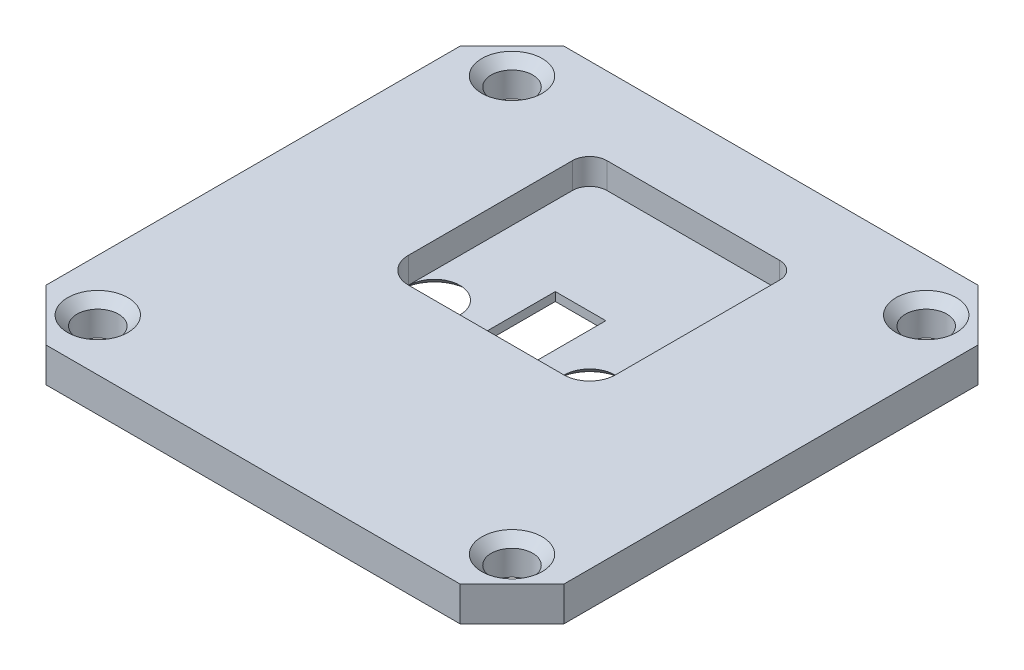
SolidWorks part; units mm, degrees
ref_plane "Front Plane" through (0, 0, 0) normal (0, 0, 1) x (1, 0, 0)
ref_plane "Top Plane" through (0, 0, 0) normal (0, 1, 0) x (1, 0, 0)
ref_plane "Right Plane" through (0, 0, 0) normal (1, 0, 0) x (0, 0, -1)
sketch "Sketch1" plane through (0, 0, 0) normal (0, 1, 0) x (1, 0, 0)
  line L0 (-11.2931, 29.7045) -> (12.7069, 29.7045)
  line L1 (12.7069, 29.7045) -> (15.7069, 26.7045)
  line L2 (15.7069, 26.7045) -> (15.7069, 2.7045)
  line L3 (15.7069, 2.7045) -> (12.7069, -0.2955)
  line L4 (12.7069, -0.2955) -> (-11.2931, -0.2955)
  line L5 (-11.2931, -0.2955) -> (-14.2931, 2.7045)
  line L6 (-14.2931, 26.7045) -> (-14.2931, 2.7045)
  line L7 (-11.2931, 29.7045) -> (-14.2931, 26.7045)
  line L9 (2.2069, 18.6402) -> (-0.719, 18.6402)
  line L10 (2.2069, 18.6402) -> (2.2069, 13.7386)
  line L11 (2.2069, 13.7386) -> (-0.719, 13.7386)
  line L12 (-0.719, 18.6402) -> (-0.719, 13.7386)
  dimension "D1" = 2.2069
  dimension "D2" = 12.7069
  dimension "D3" = 0.719
  dimension "D4" = 11.2931
  dimension "D5" = 14.2931
  dimension "D6" = 2.7045
extrude "Boss-Extrude1" add sketch "Sketch1" along normal blind 2
sketch "Sketch7" plane through (0, 2, 0) normal (0, 1, 0) x (1, 0, 0)
  line L0 (-14.2931, 26.7045) -> (-14.2931, 2.7045) construction
  line L1 (12.7069, 29.7045) -> (-11.2931, 29.7045) construction
  line L2 (15.7069, 2.7045) -> (15.7069, 26.7045) construction
  line L3 (-11.2931, -0.2955) -> (12.7069, -0.2955) construction
  circle A0 centre (-11.2931, 26.7045) radius 0.551
  circle A1 centre (-11.2931, 2.7045) radius 0.6431
  circle A2 centre (12.7069, 26.7045) radius 0.6077
  circle A3 centre (12.7069, 2.7045) radius 0.4297
  point P0 (-11.2931, 26.7045)
  point P2 (-11.2931, 2.7045)
  point P4 (12.7069, 26.7045)
  point P6 (12.7069, 2.7045)
  dimension "D9" = 1.102
  dimension "D10" = 1.2155
  dimension "D11" = 0.8595
  dimension "D12" = 1.2861
  dimension "D1" = 3
  dimension "D2" = 3
  dimension "D3" = 3
  dimension "D4" = 3
  dimension "D5" = 3
  dimension "D6" = 3
  dimension "D7" = 3
  dimension "D8" = 3
hole_wizard "CSK for M2 Flat Head Machine Screw2" positions "Sketch7" profile "Sketch8" countersink size "M2" standard "ANSI Metric"
sketch "Sketch8" plane through (-11.2931, 2, -26.7045) normal (1, 0, 0) x (0, 0, 1)
  line L0 (0, 0) -> (0, 43.651)
  line L1 (0, 43.651) -> (1.2, 42.93)
  line L2 (1.2, 42.93) -> (1.2, 0.55)
  line L3 (1.2, 0.55) -> (1.75, 0)
  line L5 (1.75, 0) -> (0, 0)
  line L6 (-1.2, 0.55) -> (-1.75, 0) construction
  line L10 (0, 43.651) -> (-1.2, 42.93) construction
  line L11 (0, -6.35) -> (0, 107.95) construction
  dimension "Hole Dia." = 2.4
  dimension "Hole Depth" = 42.93
  dimension "Near C'Sink Dia." = 3.5
  dimension "Near C'Sink Angle" = 90
  dimension "Drill Angle" = 118
sketch "Sketch9" plane through (0, 0, 0) normal (0, -1, 0) x (1, 0, 0)
  line L0 (15.7069, -2.7045) -> (15.7069, -26.7045) construction
  line L2 (12.7069, -29.7045) -> (-11.2931, -29.7045) construction
  circle A0 centre (-3.7931, -14.7045) radius 1.375
  circle A1 centre (5.2069, -14.7045) radius 1.375
  point P0 (-3.7931, -14.7045)
  point P2 (5.2069, -14.7045)
  dimension "D1" = 9
  dimension "D2" = 2.75
  dimension "D3" = 2.75
  dimension "D4" = 10.5
  dimension "D5" = 15
hole_wizard "CSK for M2 Cross Countersunk Head Screw1" positions "Sketch9" profile "Sketch10" countersink size "M2" standard "AS"
sketch "Sketch10" plane through (-3.7931, 0, -14.7045) normal (1, 0, 0) x (0, 0, -1)
  line L0 (0, 0) -> (0, 9.5262)
  line L1 (0, 9.5262) -> (1.375, 8.7)
  line L2 (1.375, 8.7) -> (1.375, 0.6036)
  line L3 (1.375, 0.6036) -> (2, 0)
  line L5 (2, 0) -> (0, 0)
  line L6 (-1.375, 0.6036) -> (-2, 0) construction
  line L10 (0, 9.5262) -> (-1.375, 8.7) construction
  line L11 (0, -6.35) -> (0, 107.95) construction
  dimension "Hole Dia." = 2.75
  dimension "Hole Depth" = 8.7
  dimension "Near C'Sink Dia." = 4
  dimension "Near C'Sink Angle" = 92
  dimension "Drill Angle" = 118
sketch "Sketch11" plane through (0, 2, 0) normal (0, 1, 0) x (1, 0, 0)
  line L0 (-5.2931, 24.2045) -> (-5.2931, 14.7045)
  line L1 (-4.2931, 25.2045) -> (5.7069, 25.2045)
  line L2 (6.7069, 24.2045) -> (6.7069, 14.7045)
  line L3 (-3.7931, 13.2045) -> (5.2069, 13.2045)
  arc A1 (-5.2931, 14.7045) -> (-3.7931, 13.2045) centre (-3.7931, 14.7045) ccw
  arc A2 (5.2069, 13.2045) -> (6.7069, 14.7045) centre (5.2069, 14.7045) ccw
  arc A3 (5.7069, 25.2045) -> (6.7069, 24.2045) centre (5.7069, 24.2045) cw
  arc A4 (-5.2931, 24.2045) -> (-4.2931, 25.2045) centre (-4.2931, 24.2045) cw
extrude "Cut-Extrude1" cut sketch "Sketch11" against normal blind 1.5
